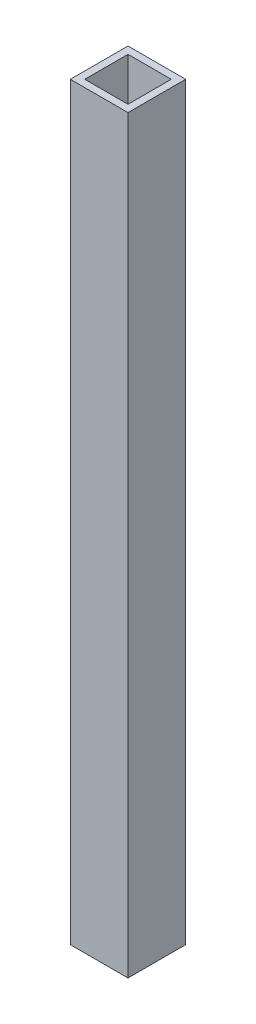
SolidWorks part; units mm, degrees
ref_plane "Front Plane" through (0, 0, 0) normal (0, 0, 1) x (1, 0, 0)
ref_plane "Top Plane" through (0, 0, 0) normal (0, 1, 0) x (1, 0, 0)
ref_plane "Right Plane" through (0, 0, 0) normal (1, 0, 0) x (0, 0, -1)
sketch "Sketch1" plane through (0, 0, 0) normal (0, 1, 0) x (1, 0, 0)
  line L0 (-9.525, 9.525) -> (9.525, 9.525)
  line L1 (-12.7, 12.7) -> (12.7, 12.7)
  line L2 (-12.7, 12.7) -> (-12.7, -12.7)
  line L3 (-12.7, -12.7) -> (12.7, -12.7)
  line L4 (12.7, 12.7) -> (12.7, -12.7)
  line L5 (9.525, 9.525) -> (9.525, -9.525)
  line L6 (-9.525, -9.525) -> (9.525, -9.525)
  line L7 (-9.525, 9.525) -> (-9.525, -9.525)
  dimension "D1" = 25.4
  dimension "D2" = 25.4
  dimension "D3" = 12.7
  dimension "D4" = 12.7
  dimension "D5" = 3.175
extrude "Boss-Extrude1" add sketch "Sketch1" along normal blind 330.2
